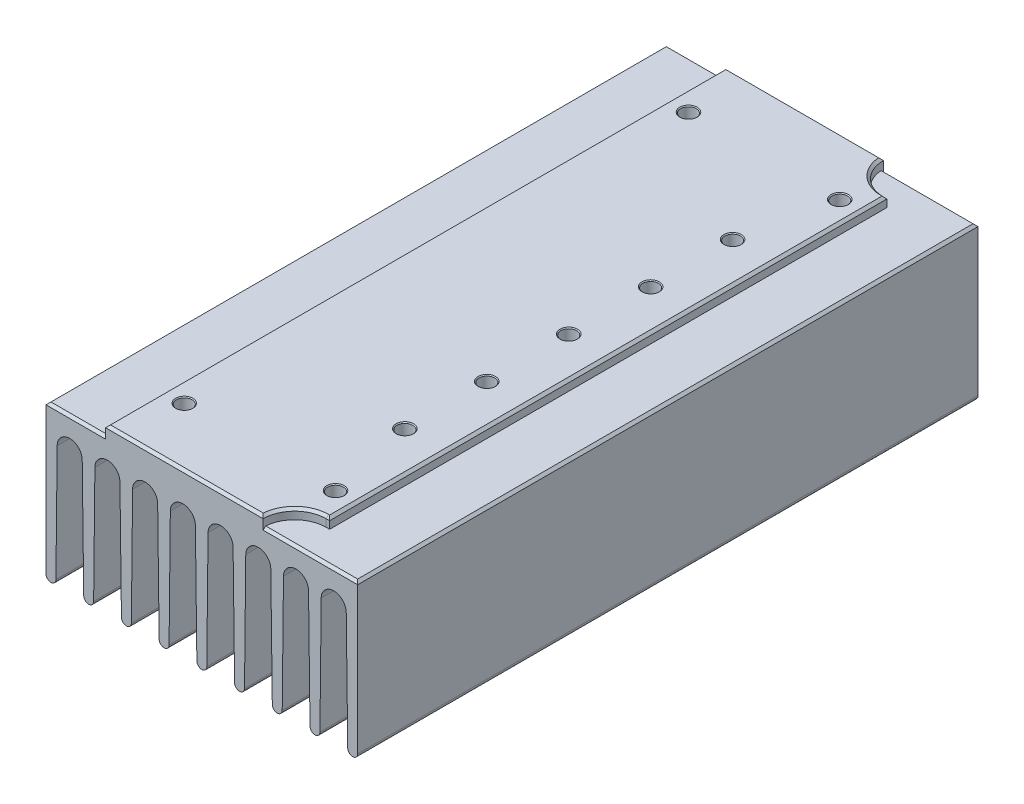
SolidWorks part; units mm, degrees
ref_plane "Спереди" through (0, 0, 0) normal (0, 0, 1) x (1, 0, 0)
ref_plane "Сверху" through (0, 0, 0) normal (0, 1, 0) x (1, 0, 0)
ref_plane "Справа" through (0, 0, 0) normal (1, 0, 0) x (0, 0, -1)
sketch "Эскиз1" plane through (0, 0, 0) normal (0, 0, 1) x (1, 0, 0)
  line L0 (-19.4, 0) -> (19.4, 0)
  line L21 (-29.4001, -32.0107) -> (-29.1482, -8.473)
  line L22 (-23.7999, -32.0128) -> (-24.1002, -8.4678)
  line L23 (-21.8001, -32.0107) -> (-21.5482, -8.473)
  line L24 (-16.1999, -32.0128) -> (-16.5002, -8.4678)
  line L25 (-14.2001, -32.0107) -> (-13.9482, -8.473)
  line L26 (-8.5999, -32.0128) -> (-8.9002, -8.4678)
  line L27 (-6.6001, -32.0107) -> (-6.3482, -8.473)
  line L28 (-0.9999, -32.0128) -> (-1.3002, -8.4678)
  line L29 (0.9999, -32.0107) -> (1.2518, -8.473)
  line L30 (6.6001, -32.0128) -> (6.2998, -8.4678)
  line L31 (8.5999, -32.0107) -> (8.8518, -8.473)
  line L32 (14.2001, -32.0128) -> (13.8998, -8.4678)
  line L33 (16.1999, -32.0107) -> (16.4518, -8.473)
  line L34 (21.8001, -32.0128) -> (21.4998, -8.4678)
  line L35 (23.7999, -32.0107) -> (24.0518, -8.473)
  line L36 (29.4001, -32.0128) -> (29.0998, -8.4678)
  line L37 (-31.4, -6.0005) -> (-31.4, -32)
  line L38 (31.4, -6.0005) -> (31.4, -32)
  line L39 (31.4, -2) -> (31.4, -6.0005)
  line L40 (-31.4, -2) -> (-31.4, -6.0005)
  line L41 (-31.4, -2) -> (-19.4, -2)
  line L42 (-19.4, -2) -> (-19.4, 0)
  line L43 (0, 5) -> (0, -35) construction
  line L44 (19.4, -2) -> (19.4, 0)
  line L45 (31.4, -2) -> (19.4, -2)
  arc A17 (-29.1482, -8.473) -> (-24.1002, -8.4678) centre (-26.6242, -8.5) cw
  arc A18 (-21.5482, -8.473) -> (-16.5002, -8.4678) centre (-19.0242, -8.5) cw
  arc A19 (-13.9482, -8.473) -> (-8.9002, -8.4678) centre (-11.4242, -8.5) cw
  arc A20 (-6.3482, -8.473) -> (-1.3002, -8.4678) centre (-3.8242, -8.5) cw
  arc A21 (1.2518, -8.473) -> (6.2998, -8.4678) centre (3.7758, -8.5) cw
  arc A22 (8.8518, -8.473) -> (13.8998, -8.4678) centre (11.3758, -8.5) cw
  arc A23 (16.4518, -8.473) -> (21.4998, -8.4678) centre (18.9758, -8.5) cw
  arc A24 (24.0518, -8.473) -> (29.0998, -8.4678) centre (26.5758, -8.5) cw
  arc A25 (-29.4001, -32.0107) -> (-31.4, -32) centre (-30.4, -32) cw
  arc A26 (-21.8001, -32.0107) -> (-23.7999, -32.0128) centre (-22.8, -32) cw
  arc A27 (-14.2001, -32.0107) -> (-16.1999, -32.0128) centre (-15.2, -32) cw
  arc A28 (-6.6001, -32.0107) -> (-8.5999, -32.0128) centre (-7.6, -32) cw
  arc A29 (0.9999, -32.0107) -> (-0.9999, -32.0128) centre (0, -32) cw
  arc A30 (8.5999, -32.0107) -> (6.6001, -32.0128) centre (7.6, -32) cw
  arc A31 (16.1999, -32.0107) -> (14.2001, -32.0128) centre (15.2, -32) cw
  arc A32 (23.7999, -32.0107) -> (21.8001, -32.0128) centre (22.8, -32) cw
  arc A33 (31.4, -32) -> (29.4001, -32.0128) centre (30.4, -32) cw
extrude "Бобышка-Вытянуть1" add sketch "Эскиз1" against normal mid plane 125
hole_wizard "Сверло под метчик  спиральное M31" positions "Эскиз2" profile "Эскиз3" hole size "M3x0.5" standard "DIN"
sketch "Эскиз2" plane through (0, 0, 0) normal (0, 1, 0) x (1, 0, 0)
  point P0 (11.43, 0)
  point P11 (11.43, -16.51)
  point P12 (11.43, -33.02)
  point P18 (11.43, 16.51)
  point P19 (11.43, 33.02)
  point P30 (15.24, 50.8)
  point P44 (-15.24, 50.8)
  point P45 (-15.24, -50.8)
  point P46 (15.24, -50.8)
  dimension "D1" = 3
  dimension "D2" = 3
  dimension "D3" = 2
  dimension "D4" = 2
sketch "Эскиз3" plane through (11.43, 0, 0) normal (1, 0, 0) x (0, 0, 1)
  line L0 (0, 0) -> (0, 10.9464)
  line L1 (0, 10.9464) -> (1.575, 10)
  line L2 (1.575, 10) -> (1.575, 0.175)
  line L3 (1.575, 0.175) -> (1.75, 0)
  line L5 (1.75, 0) -> (0, 0)
  line L6 (-1.575, 0.175) -> (-1.75, 0) construction
  line L10 (0, 10.9464) -> (-1.575, 10) construction
  line L11 (0, -6.35) -> (0, 107.95) construction
  dimension "Диаметр отверстия" = 3.15
  dimension "Глубина отверстия" = 10
  dimension "Диаметр передней зенковки" = 3.5
  dimension "Угол передней зенковки" = 90
  dimension "Угол заточки сверла" = 118
sketch "Эскиз6" plane through (0, 0, 0) normal (0, 1, 0) x (1, 0, 0)
  line L0 (19.4, 62.5) -> (-19.4, 62.5) construction
  line L1 (18.7, 62.5) -> (31.4, 62.5)
  line L3 (18.7, 56.15) -> (31.4, 56.15)
  line L4 (31.4, 62.5) -> (31.4, 56.15)
  line L5 (31.4, 62.5) -> (31.4, -62.5) construction
  line L11 (12.35, 62.5) -> (18.7, 62.5)
  line L12 (-18.15, 0) -> (18.15, 0) construction
  line L13 (12.35, -62.5) -> (18.7, -62.5)
  line L14 (31.4, -62.5) -> (31.4, -56.15)
  line L15 (18.7, -56.15) -> (31.4, -56.15)
  line L16 (18.7, -62.5) -> (31.4, -62.5)
  arc A0 (18.7, 56.15) -> (12.35, 62.5) centre (18.7, 62.5) cw
  arc A1 (18.7, -56.15) -> (12.35, -62.5) centre (18.7, -62.5) ccw
  dimension "D1" = 6.35
  dimension "D2" = 12.7
extrude "Вырез-Вытянуть2" cut sketch "Эскиз6" against normal up to surface (2 mm away) up to face at (25.4, -2, 0)
chamfer "Фаска1" distance 0.5 angle 45 14 edges at (-25.4, -2, 62.5) (-25.4, -2, -62.5) (-31.4, -2, 0) (21.875, -2, 62.5) (21.875, -2, -62.5) (31.4, -2, 0) (-3.525, 0, 62.5) (-19.4, 0, 0) (-3.525, 0, -62.5) (19.4, 0, 0) (19.05, 0, -56.15) (14.2099, 0, -58.0099) (14.2099, 0, 58.0099) (19.05, 0, 56.15)
